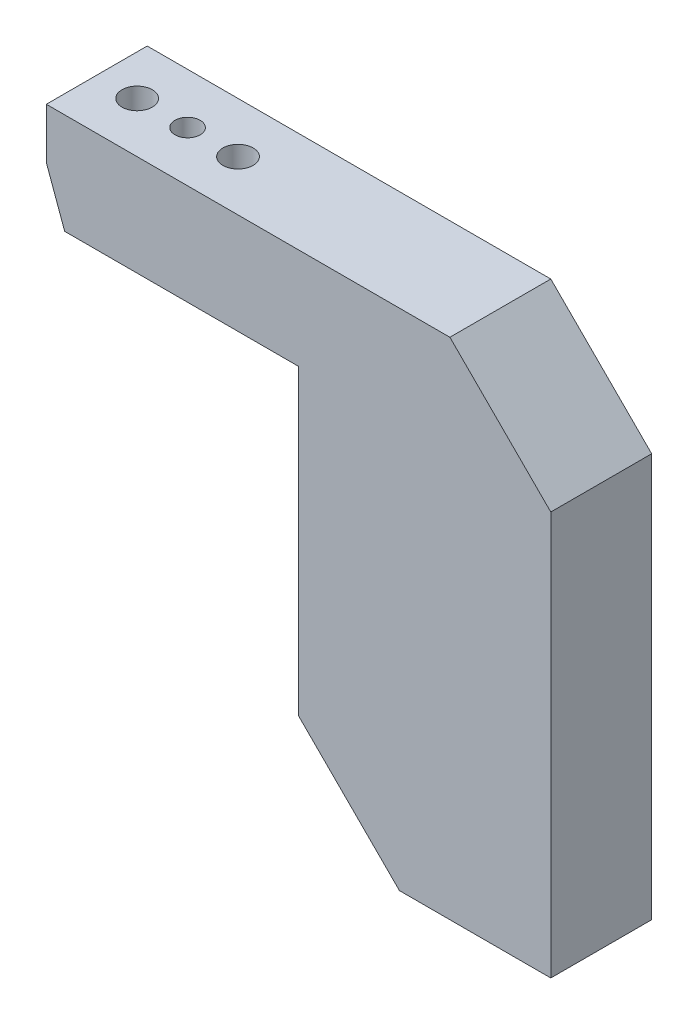
SolidWorks part; units mm, degrees
material "Q235A"
ref_plane "前视" through (0, 0, 0) normal (0, 0, 1) x (1, 0, 0)
ref_plane "上视" through (0, 0, 0) normal (0, 1, 0) x (1, 0, 0)
ref_plane "右视" through (0, 0, 0) normal (1, 0, 0) x (0, 0, -1)
sketch "草图1" plane through (0, 0, 0) normal (0, 0, 1) x (1, 0, 0)
  line L1 (50, -50) -> (-50, -50)
  line L2 (50, -50) -> (50, 50)
  line L3 (50, 50) -> (-50, 50)
  line L4 (-50, -50) -> (-50, 50)
  line L5 (50, -50) -> (-50, 50) construction
  line L6 (50, 50) -> (-50, -50) construction
  point P0 (0, 0)
  dimension "D1" = 100
  dimension "D2" = 100
extrude "凸台-拉伸1" add sketch "草图1" along normal blind 20
hole_wizard "大小mm 暗销孔1" positions "草图3" profile "草图2" hole size "Ø6.0" standard "GB"
sketch "草图3" plane through (0, 50, 0) normal (0, 1, 0) x (1, 0, 0)
  line L0 (50, -20) -> (-50, -20) construction
  line L1 (-50, -20) -> (-50, 0) construction
  point P0 (-22, -10)
  point P2 (-42, -10)
  dimension "D1" = 20
  dimension "D2" = 10
  dimension "D3" = 8
sketch "草图2" plane through (-22, 50, 10) normal (1, 0, 0) x (0, 0, 1)
  line L0 (0, 0) -> (0, 21.8026)
  line L1 (0, 21.8026) -> (3, 20)
  line L2 (3, 20) -> (3, 0)
  line L5 (3, 0) -> (0, 0)
  line L10 (0, 21.8026) -> (-3, 20) construction
  line L11 (0, -6.35) -> (0, 107.95) construction
  dimension "孔直径" = 6
  dimension "孔深度" = 20
  dimension "导头角度" = 118
hole_wizard "M6 螺纹孔1" positions "草图5" profile "草图4" tap size "M6" standard "GB"
sketch "草图5" plane through (0, 50, 0) normal (0, 1, 0) x (1, 0, 0)
  line L0 (50, -20) -> (-50, -20) construction
  circle A0 centre (-42, -10) radius 3 construction
  point P0 (-32, -10)
  dimension "D1" = 10
  dimension "D2" = 10
sketch "草图4" plane through (-32, 50, 10) normal (1, 0, 0) x (0, 0, 1)
  line L0 (0, 0) -> (0, 16.5022)
  line L1 (0, 16.5022) -> (2.5, 15)
  line L2 (2.5, 15) -> (2.5, 0)
  line L5 (2.5, 0) -> (0, 0)
  line L10 (0, 16.5022) -> (-2.5, 15) construction
  line L11 (0, -6.35) -> (0, 107.95) construction
  dimension "螺纹孔钻头直径" = 5
  dimension "螺纹孔钻头深度" = 15
  dimension "导头角度" = 118
cosmetic thread "孔螺蚊线1" parameters "D1"=12, "D2"=6
sketch "草图6" plane through (0, 0, 0) normal (0, 0, -1) x (-1, 0, 0)
  line L0 (50, 50) -> (50, -50) construction
  line L1 (50, 30) -> (0, 30)
  line L2 (50, 30) -> (50, -50)
  line L3 (50, -50) -> (0, -50)
  line L4 (0, 30) -> (0, -50)
  line L5 (50, -50) -> (-50, -50) construction
  dimension "D1" = 20
  dimension "D2" = 50
extrude "切除-拉伸1" cut sketch "草图6" against normal through all
chamfer "倒角1" distance 10 angle 20 1 edges at (-50, 30, 10)
chamfer "倒角2" distance 20 angle 45 1 edges at (0, -50, 10)
chamfer "倒角3" distance 20 angle 45 1 edges at (50, 50, 10)
